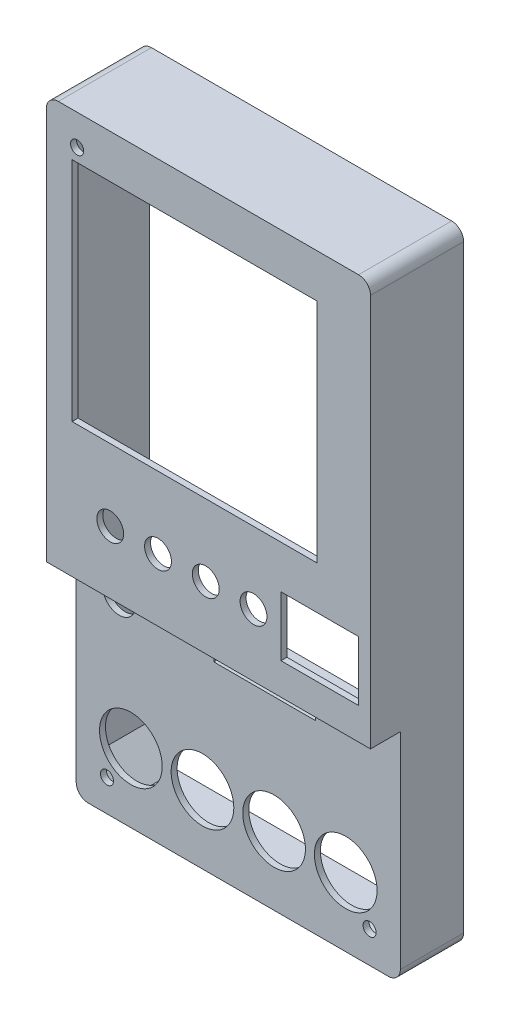
SolidWorks part; units mm, degrees
ref_plane "Přední rovina" through (0, 0, 0) normal (0, 0, 1) x (1, 0, 0)
ref_plane "Horní rovina" through (0, 0, 0) normal (0, 1, 0) x (1, 0, 0)
ref_plane "Pravá rovina" through (0, 0, 0) normal (1, 0, 0) x (0, 0, -1)
sketch "Skica1" plane through (0, 0, 0) normal (0, 0, 1) x (1, 0, 0)
  line L1 (0, 0) -> (54.3, 0)
  line L2 (0, 0) -> (0, 36.5)
  line L3 (0, 36.5) -> (54.3, 36.5)
  line L4 (54.3, 0) -> (54.3, 36.5)
  dimension "D1" = 36.5
  dimension "D2" = 54.3
extrude "Přidat vysunutím1" add sketch "Skica1" along normal blind 1
sketch "Skica4" plane through (0, 0, 0) normal (0, 0, 1) x (1, 0, 0)
  line L0 (0, 0) -> (54.3, 0) construction
  line L5 (0, 36.5) -> (54.3, 36.5)
  line L6 (0, 36.5) -> (0, 104.3)
  line L7 (0, 104.3) -> (54.3, 104.3)
  line L8 (54.3, 36.5) -> (54.3, 104.3)
  line L9 (1.65, 38.15) -> (52.65, 38.15)
  line L10 (1.65, 38.15) -> (1.65, 102.65)
  line L11 (1.65, 102.65) -> (52.65, 102.65)
  line L12 (52.65, 38.15) -> (52.65, 102.65)
  point P10 (0, 0)
  dimension "D1" = 1.65
  dimension "D2" = 1.65
  dimension "D3" = 1.65
  dimension "D4" = 1.65
  dimension "D5" = 104.3
extrude "Přidat vysunutím2" add sketch "Skica4" along normal blind 6
sketch "Skica5" plane through (0, 0, 6) normal (0, 0, 1) x (1, 0, 0)
  line L1 (1.65, 102.65) -> (52.65, 102.65)
  line L2 (1.65, 102.65) -> (1.65, 38.15)
  line L3 (1.65, 38.15) -> (52.65, 38.15)
  line L4 (52.65, 102.65) -> (52.65, 38.15)
extrude "Přidat vysunutím3" add sketch "Skica5" against normal blind 1
sketch "Skica2" plane through (0, 0, 1) normal (0, 0, 1) x (1, 0, 0)
  line L3 (0, 0) -> (54.3, 0) construction
  line L4 (0, 36.5) -> (0, 0) construction
  line L5 (54.3, 0) -> (54.3, 36.5) construction
  circle A2 centre (49.15, 5.3) radius 1.1
  circle A3 centre (5.15, 5.3) radius 1.1
  point P8 (0, 0)
  point P9 (0, 0)
  point P10 (0, 0)
  point P11 (0, 0)
  point P12 (0, 0)
  dimension "D1" = 5.15
  dimension "D2" = 5.15
  dimension "D3" = 2.2
  dimension "D4" = 2.2
  dimension "D8" = 5.3
extrude "Odebrat vysunutím1" cut sketch "Skica2" against normal blind 1
sketch "Skica3" plane through (0, 0, 1) normal (0, 0, 1) x (1, 0, 0)
  line L0 (21.15, 11.5) -> (33.15, 11.5) construction
  line L1 (0, 0) -> (54.3, 0) construction
  line L2 (0, 36.5) -> (0, 0) construction
  line L3 (23.05, 34.5) -> (40.05, 34.5)
  line L4 (23.05, 34.5) -> (23.05, 31)
  line L5 (23.05, 31) -> (40.05, 31)
  line L6 (40.05, 34.5) -> (40.05, 31)
  line L7 (54.3, 0) -> (54.3, 36.5) construction
  circle A0 centre (9.15, 11.5) radius 5.25
  circle A1 centre (21.15, 11.5) radius 5.25
  circle A2 centre (33.15, 11.5) radius 5.25
  circle A3 centre (45.15, 11.5) radius 5.25
  circle A4 centre (7.2, 32.6) radius 2.75
  point P8 (27.15, 11.5)
  point P11 (27.15, 0)
  dimension "D1" = 10.5
  dimension "D2" = 10.5
  dimension "D3" = 10.5
  dimension "D4" = 10.5
  dimension "D9" = 5.5
  dimension "D5" = 12
  dimension "D6" = 12
  dimension "D7" = 12
  dimension "D8" = 11.5
  dimension "D10" = 17
  dimension "D11" = 3.5
  dimension "D12" = 7.2
  dimension "D13" = 14.25
  dimension "D14" = 31
  dimension "D15" = 32.6
extrude "Odebrat vysunutím2" cut sketch "Skica3" against normal blind 1
sketch "Skica6" plane through (0, 0, 6) normal (0, 0, 1) x (1, 0, 0)
  line L0 (54.3, 104.3) -> (0, 104.3) construction
  line L1 (4.3, 97) -> (45.3, 97)
  line L2 (4.3, 97) -> (4.3, 59)
  line L3 (4.3, 59) -> (45.3, 59)
  line L4 (45.3, 97) -> (45.3, 59)
  line L5 (14.3, 97) -> (35.3, 97)
  line L6 (14.3, 97) -> (14.3, 100.5)
  line L7 (14.3, 100.5) -> (35.3, 100.5)
  line L8 (35.3, 97) -> (35.3, 100.5)
  line L9 (14.3, 59) -> (35.3, 59)
  line L10 (14.3, 59) -> (14.3, 55.5)
  line L11 (14.3, 55.5) -> (35.3, 55.5)
  line L12 (35.3, 59) -> (35.3, 55.5)
  line L13 (39.3, 41.8) -> (52.3, 41.8)
  line L14 (39.3, 41.8) -> (39.3, 51.8)
  line L15 (39.3, 51.8) -> (52.3, 51.8)
  line L16 (52.3, 41.8) -> (52.3, 51.8)
  line L18 (0, 104.3) -> (0, 36.5) construction
  line L19 (54.3, 36.5) -> (54.3, 104.3) construction
  line L20 (0, 36.5) -> (54.3, 36.5) construction
  circle A0 centre (5.15, 99.2) radius 1.1
  circle A1 centre (49.15, 99.2) radius 1.1
  circle A2 centre (10.7, 47) radius 2.25
  circle A3 centre (18.7, 47) radius 2.25
  circle A4 centre (26.7, 47) radius 2.25
  circle A5 centre (34.7, 47) radius 2.25
  point P28 (0, 0)
  point P29 (0, 0)
  point P34 (0, 101.0965)
  point P37 (0, 0)
  point P40 (24.8, 100.5)
  point P41 (24.8, 97)
  dimension "D4" = 2.2
  dimension "D5" = 2.2
  dimension "D11" = 4.5
  dimension "D12" = 4.5
  dimension "D13" = 4.5
  dimension "D14" = 4.5
  dimension "D1" = 5.1
  dimension "D2" = 5.15
  dimension "D3" = 5.15
  dimension "D6" = 41
  dimension "D7" = 38
  dimension "D8" = 21
  dimension "D9" = 3.5
  dimension "D10" = 3.5
  dimension "D15" = 8
  dimension "D16" = 8
  dimension "D17" = 8
  dimension "D18" = 10.5
  dimension "D19" = 10.7
  dimension "D20" = 10
  dimension "D21" = 13
  dimension "D22" = 5.3
  dimension "D23" = 2
  dimension "D24" = 3.8
  dimension "D25" = 4.3
extrude "Odebrat vysunutím3" cut sketch "Skica6" against normal through all contours L4 L1 L2 L3 | A5 | A4 | A3 | A2 | A0 | L13 L16 L15 L14
sketch "Skica8" plane through (0, 0, 0) normal (0, 0, -1) x (-1, 0, 0)
  line L0 (-54.3, 0) -> (-54.3, 104.3) construction
  line L1 (0, 0) -> (-54.3, 0)
  line L2 (0, 0) -> (0, 104.3)
  line L3 (0, 104.3) -> (-54.3, 104.3)
  line L4 (-54.3, 0) -> (-54.3, 104.3)
  line L5 (-54.3, 104.3) -> (0, 104.3) construction
  line L7 (-1.65, 102.65) -> (-52.65, 102.65)
  line L8 (-1.65, 102.65) -> (-1.65, 1.65)
  line L9 (-1.65, 1.65) -> (-52.65, 1.65)
  line L10 (-52.65, 102.65) -> (-52.65, 1.65)
  dimension "D1" = 1.65
  dimension "D2" = 1.65
extrude "Přidat vysunutím4" add sketch "Skica8" along normal blind 9.6
fillet "Zaoblit1" radius 2 4 edges at (54.3, 0, -4.3) (0, 0, -4.3) (0, 104.3, -1.8) (54.3, 104.3, -1.8)
sketch "Skica9" plane through (0, 0, 0) normal (0, 0, -1) x (-1, 0, 0)
  line L0 (-1.65, 1.65) -> (-1.65, 6.35)
  line L1 (-1.65, 1.65) -> (-1.65, 38.15) construction
  line L2 (-1.65, 6.35) -> (-6.35, 1.65)
  line L3 (-52.65, 1.65) -> (-1.65, 1.65) construction
  line L4 (-6.35, 1.65) -> (-1.65, 1.65)
  line L5 (-52.65, 1.65) -> (-52.65, 6.35)
  line L6 (-52.65, 38.15) -> (-52.65, 1.65) construction
  line L7 (-52.65, 6.35) -> (-47.95, 1.65)
  line L8 (-47.95, 1.65) -> (-52.65, 1.65)
  line L9 (-15.9, 1.65) -> (-15.9, 18.75) construction
  line L10 (-20.9, 18.75) -> (-15.9, 18.75)
  line L11 (-20.9, 18.75) -> (-20.9, 23.75)
  line L12 (-20.9, 23.75) -> (-15.9, 23.75)
  line L13 (-15.9, 18.75) -> (-15.9, 23.75)
  line L14 (-9.15, 16.75) -> (-21.15, 16.75) construction
  circle A0 centre (-21.15, 11.5) radius 5.25 construction
  circle A1 centre (-9.15, 11.5) radius 5.25 construction
  dimension "D1" = 4.7
  dimension "D2" = 4.7
  dimension "D3" = 5
  dimension "D4" = 5
  dimension "D5" = 2
extrude "Přidat vysunutím5" add sketch "Skica9" along normal blind 9.6
